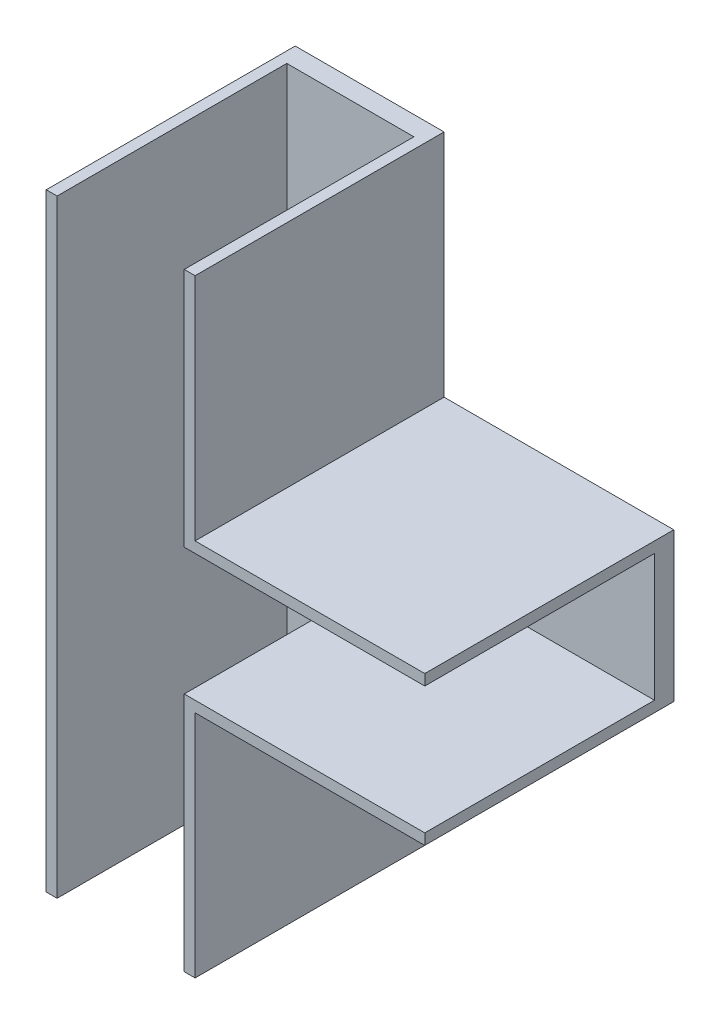
SolidWorks part; units mm, degrees
ref_plane "Front" through (0, 0, 0) normal (0, 0, 1) x (1, 0, 0)
ref_plane "Top" through (0, 0, 0) normal (0, 1, 0) x (1, 0, 0)
ref_plane "Right" through (0, 0, 0) normal (1, 0, 0) x (0, 0, -1)
sketch "Sketch1" plane through (0, 0, 0) normal (0, 0, 1) x (1, 0, 0)
  line L0 (0, 0) -> (0, 25.2222)
  line L1 (0, 25.2222) -> (6.1722, 25.2222)
  line L2 (6.1722, 25.2222) -> (6.1722, 15.6972)
  line L3 (6.1722, 15.6972) -> (15.6972, 15.6972)
  line L4 (15.6972, 15.6972) -> (15.6972, 9.525)
  line L5 (15.6972, 9.525) -> (6.1722, 9.525)
  line L6 (6.1722, 9.525) -> (6.1722, 0)
  line L7 (6.1722, 0) -> (0, 0)
  dimension "D1" = 6.1722
  dimension "D2" = 6.1722
  dimension "D3" = 6.1722
  dimension "D4" = 9.525
  dimension "D5" = 9.525
extrude "Boss-Extrude1" add sketch "Sketch1" along normal blind 0.8
sketch "Sketch2" plane through (0, 0, 0.8) normal (0, 0, 1) x (1, 0, 0)
  line L16 (0, 0) -> (6.1722, 0)
  line L17 (6.1722, 0) -> (6.1722, 9.525)
  line L18 (6.1722, 9.525) -> (15.6972, 9.525)
  line L19 (15.6972, 9.525) -> (15.6972, 15.6972)
  line L20 (15.6972, 15.6972) -> (6.1722, 15.6972)
  line L21 (6.1722, 15.6972) -> (6.1722, 25.2222)
  line L22 (6.1722, 25.2222) -> (0, 25.2222)
  line L23 (0, 25.2222) -> (0, 0)
  line L24 (6.1722, 25.2222) -> (0, 25.2222) construction
  line L25 (6.1722, 0) -> (6.1722, 9.525)
  line L26 (6.1722, 9.525) -> (15.6972, 9.525)
  line L27 (15.6972, 9.525) -> (15.6972, 15.6972) construction
  line L28 (15.6972, 15.6972) -> (6.1722, 15.6972)
  line L29 (6.1722, 15.6972) -> (6.1722, 25.2222)
  line L30 (0, 0) -> (6.1722, 0) construction
  line L31 (0, 25.2222) -> (0, 0)
  line L32 (0, 25.2222) -> (0.45, 25.2222)
  line L33 (6.1722, 25.2222) -> (5.7222, 25.2222)
  line L34 (15.6972, 15.6972) -> (15.6972, 15.2472)
  line L35 (15.6972, 9.975) -> (15.6972, 9.525)
  line L36 (0, 0) -> (0.45, 0)
  line L37 (5.7222, 0) -> (6.1722, 0)
  line L40 (0.45, 0.45) -> (5.7222, 0.45)
  line L41 (5.7222, 0.45) -> (5.7222, 9.975)
  line L42 (5.7222, 9.975) -> (15.2472, 9.975)
  line L43 (15.2472, 9.975) -> (15.2472, 15.2472)
  line L44 (15.2472, 15.2472) -> (5.7222, 15.2472)
  line L45 (5.7222, 15.2472) -> (5.7222, 24.7722)
  line L46 (5.7222, 24.7722) -> (0.45, 24.7722)
  line L47 (0.45, 24.7722) -> (0.45, 0.45)
  line L49 (5.7222, 0) -> (5.7222, 9.975)
  line L50 (5.7222, 9.975) -> (15.6972, 9.975)
  line L52 (15.6972, 15.2472) -> (5.7222, 15.2472)
  line L53 (5.7222, 15.2472) -> (5.7222, 25.2222)
  line L55 (0.45, 25.2222) -> (0.45, 0)
  dimension "D1" = 0
  dimension "D2" = 0.45
extrude "Boss-Extrude2" add sketch "Sketch2" along normal blind 9.525
